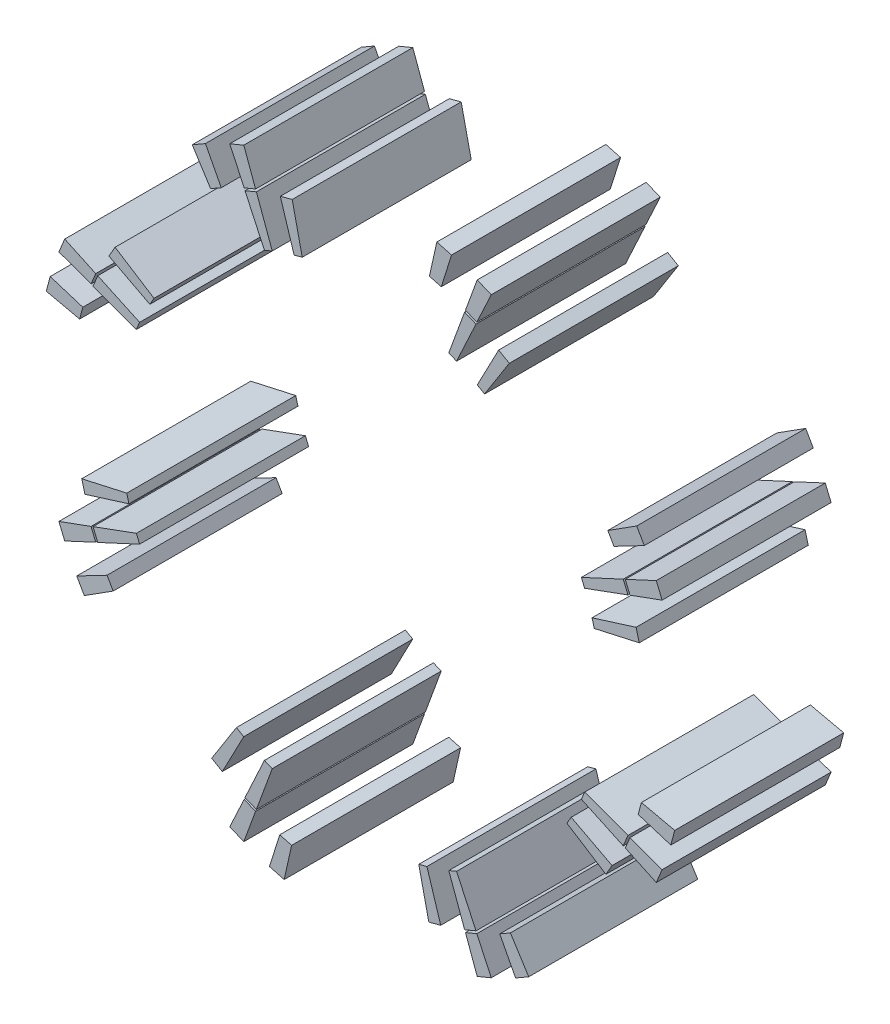
SolidWorks part; units mm, degrees
ref_plane "Спереди" through (0, 0, 0) normal (0, 0, 1) x (1, 0, 0)
ref_plane "Сверху" through (0, 0, 0) normal (0, 1, 0) x (1, 0, 0)
ref_plane "Справа" through (0, 0, 0) normal (1, 0, 0) x (0, 0, -1)
sketch "Эскиз1" plane through (0, 0, 0) normal (0, 0, 1) x (1, 0, 0)
  line L0 (41.4922, 10.3414) -> (49.4854, 12.1292)
  line L1 (49.4854, 12.1292) -> (48.9202, 14.2385)
  line L2 (48.9202, 14.2385) -> (41.104, 11.7902)
  line L3 (41.104, 11.7902) -> (41.4922, 10.3414)
  line L4 (47.8376, 18.6332) -> (53.5402, 20.7158)
  line L5 (53.5402, 20.7158) -> (52.507, 23.2103)
  line L6 (52.507, 23.2103) -> (47.002, 20.6506)
  line L7 (47.002, 20.6506) -> (47.8376, 18.6332)
  line L8 (39.7874, 15.6687) -> (47.4788, 18.4846)
  line L9 (47.4788, 18.4846) -> (46.6432, 20.502)
  line L10 (46.6432, 20.502) -> (39.2134, 17.0545)
  line L11 (39.2134, 17.0545) -> (39.7874, 15.6687)
  line L12 (44.9963, 24.7179) -> (50.3782, 27.527)
  line L13 (50.3782, 27.527) -> (49.0282, 29.8653)
  line L14 (49.0282, 29.8653) -> (43.9044, 26.609)
  line L15 (43.9044, 26.609) -> (44.9963, 24.7179)
  line L16 (22.027, 36.6519) -> (26.4148, 43.5681)
  line L17 (26.4148, 43.5681) -> (24.5237, 44.6599)
  line L18 (24.5237, 44.6599) -> (20.728, 37.4019)
  line L19 (20.728, 37.4019) -> (22.027, 36.6519)
  line L20 (20.6506, 47.002) -> (23.2103, 52.507)
  line L21 (23.2103, 52.507) -> (20.7158, 53.5402)
  line L22 (20.7158, 53.5402) -> (18.6332, 47.8376)
  line L23 (18.6332, 47.8376) -> (20.6506, 47.002)
  line L24 (17.0545, 39.2134) -> (20.502, 46.6432)
  line L25 (20.502, 46.6432) -> (18.4846, 47.4788)
  line L26 (18.4846, 47.4788) -> (15.6687, 39.7874)
  line L27 (15.6687, 39.7874) -> (17.0545, 39.2134)
  line L28 (14.339, 49.2953) -> (16.1582, 55.0873)
  line L29 (16.1582, 55.0873) -> (13.5502, 55.7861)
  line L30 (13.5502, 55.7861) -> (12.2298, 49.8605)
  line L31 (12.2298, 49.8605) -> (14.339, 49.2953)
  line L32 (-10.3414, 41.4922) -> (-12.1292, 49.4854)
  line L33 (-12.1292, 49.4854) -> (-14.2385, 48.9202)
  line L34 (-14.2385, 48.9202) -> (-11.7902, 41.104)
  line L35 (-11.7902, 41.104) -> (-10.3414, 41.4922)
  line L36 (-18.6332, 47.8376) -> (-20.7158, 53.5402)
  line L37 (-20.7158, 53.5402) -> (-23.2103, 52.507)
  line L38 (-23.2103, 52.507) -> (-20.6506, 47.002)
  line L39 (-20.6506, 47.002) -> (-18.6332, 47.8376)
  line L40 (-15.6687, 39.7874) -> (-18.4846, 47.4788)
  line L41 (-18.4846, 47.4788) -> (-20.502, 46.6432)
  line L42 (-20.502, 46.6432) -> (-17.0545, 39.2134)
  line L43 (-17.0545, 39.2134) -> (-15.6687, 39.7874)
  line L44 (-24.7179, 44.9963) -> (-27.527, 50.3782)
  line L45 (-27.527, 50.3782) -> (-29.8653, 49.0282)
  line L46 (-29.8653, 49.0282) -> (-26.609, 43.9044)
  line L47 (-26.609, 43.9044) -> (-24.7179, 44.9963)
  line L48 (-36.6519, 22.027) -> (-43.5681, 26.4148)
  line L49 (-43.5681, 26.4148) -> (-44.6599, 24.5237)
  line L50 (-44.6599, 24.5237) -> (-37.4019, 20.728)
  line L51 (-37.4019, 20.728) -> (-36.6519, 22.027)
  line L52 (-47.002, 20.6506) -> (-52.507, 23.2103)
  line L53 (-52.507, 23.2103) -> (-53.5402, 20.7158)
  line L54 (-53.5402, 20.7158) -> (-47.8376, 18.6332)
  line L55 (-47.8376, 18.6332) -> (-47.002, 20.6506)
  line L56 (-39.2134, 17.0545) -> (-46.6432, 20.502)
  line L57 (-46.6432, 20.502) -> (-47.4788, 18.4846)
  line L58 (-47.4788, 18.4846) -> (-39.7874, 15.6687)
  line L59 (-39.7874, 15.6687) -> (-39.2134, 17.0545)
  line L60 (-49.2953, 14.339) -> (-55.0873, 16.1582)
  line L61 (-55.0873, 16.1582) -> (-55.7861, 13.5502)
  line L62 (-55.7861, 13.5502) -> (-49.8605, 12.2298)
  line L63 (-49.8605, 12.2298) -> (-49.2953, 14.339)
  line L64 (-41.4922, -10.3414) -> (-49.4854, -12.1292)
  line L65 (-49.4854, -12.1292) -> (-48.9202, -14.2385)
  line L66 (-48.9202, -14.2385) -> (-41.104, -11.7902)
  line L67 (-41.104, -11.7902) -> (-41.4922, -10.3414)
  line L68 (-47.8376, -18.6332) -> (-53.5402, -20.7158)
  line L69 (-53.5402, -20.7158) -> (-52.507, -23.2103)
  line L70 (-52.507, -23.2103) -> (-47.002, -20.6506)
  line L71 (-47.002, -20.6506) -> (-47.8376, -18.6332)
  line L72 (-39.7874, -15.6687) -> (-47.4788, -18.4846)
  line L73 (-47.4788, -18.4846) -> (-46.6432, -20.502)
  line L74 (-46.6432, -20.502) -> (-39.2134, -17.0545)
  line L75 (-39.2134, -17.0545) -> (-39.7874, -15.6687)
  line L76 (-44.9963, -24.7179) -> (-50.3782, -27.527)
  line L77 (-50.3782, -27.527) -> (-49.0282, -29.8653)
  line L78 (-49.0282, -29.8653) -> (-43.9044, -26.609)
  line L79 (-43.9044, -26.609) -> (-44.9963, -24.7179)
  line L80 (-22.027, -36.6519) -> (-26.4148, -43.5681)
  line L81 (-26.4148, -43.5681) -> (-24.5237, -44.6599)
  line L82 (-24.5237, -44.6599) -> (-20.728, -37.4019)
  line L83 (-20.728, -37.4019) -> (-22.027, -36.6519)
  line L84 (-20.6506, -47.002) -> (-23.2103, -52.507)
  line L85 (-23.2103, -52.507) -> (-20.7158, -53.5402)
  line L86 (-20.7158, -53.5402) -> (-18.6332, -47.8376)
  line L87 (-18.6332, -47.8376) -> (-20.6506, -47.002)
  line L88 (-17.0545, -39.2134) -> (-20.502, -46.6432)
  line L89 (-20.502, -46.6432) -> (-18.4846, -47.4788)
  line L90 (-18.4846, -47.4788) -> (-15.6687, -39.7874)
  line L91 (-15.6687, -39.7874) -> (-17.0545, -39.2134)
  line L92 (-14.339, -49.2953) -> (-16.1582, -55.0873)
  line L93 (-16.1582, -55.0873) -> (-13.5502, -55.7861)
  line L94 (-13.5502, -55.7861) -> (-12.2298, -49.8605)
  line L95 (-12.2298, -49.8605) -> (-14.339, -49.2953)
  line L96 (10.3414, -41.4922) -> (12.1292, -49.4854)
  line L97 (12.1292, -49.4854) -> (14.2385, -48.9202)
  line L98 (14.2385, -48.9202) -> (11.7902, -41.104)
  line L99 (11.7902, -41.104) -> (10.3414, -41.4922)
  line L100 (18.6332, -47.8376) -> (20.7158, -53.5402)
  line L101 (20.7158, -53.5402) -> (23.2103, -52.507)
  line L102 (23.2103, -52.507) -> (20.6506, -47.002)
  line L103 (20.6506, -47.002) -> (18.6332, -47.8376)
  line L104 (15.6687, -39.7874) -> (18.4846, -47.4788)
  line L105 (18.4846, -47.4788) -> (20.502, -46.6432)
  line L106 (20.502, -46.6432) -> (17.0545, -39.2134)
  line L107 (17.0545, -39.2134) -> (15.6687, -39.7874)
  line L108 (24.7179, -44.9963) -> (27.527, -50.3782)
  line L109 (27.527, -50.3782) -> (29.8653, -49.0282)
  line L110 (29.8653, -49.0282) -> (26.609, -43.9044)
  line L111 (26.609, -43.9044) -> (24.7179, -44.9963)
  line L112 (36.6519, -22.027) -> (43.5681, -26.4148)
  line L113 (43.5681, -26.4148) -> (44.6599, -24.5237)
  line L114 (44.6599, -24.5237) -> (37.4019, -20.728)
  line L115 (37.4019, -20.728) -> (36.6519, -22.027)
  line L116 (47.002, -20.6506) -> (52.507, -23.2103)
  line L117 (52.507, -23.2103) -> (53.5402, -20.7158)
  line L118 (53.5402, -20.7158) -> (47.8376, -18.6332)
  line L119 (47.8376, -18.6332) -> (47.002, -20.6506)
  line L120 (39.2134, -17.0545) -> (46.6432, -20.502)
  line L121 (46.6432, -20.502) -> (47.4788, -18.4846)
  line L122 (47.4788, -18.4846) -> (39.7874, -15.6687)
  line L123 (39.7874, -15.6687) -> (39.2134, -17.0545)
  line L124 (49.2953, -14.339) -> (55.0873, -16.1582)
  line L125 (55.0873, -16.1582) -> (55.7861, -13.5502)
  line L126 (55.7861, -13.5502) -> (49.8605, -12.2298)
  line L127 (49.8605, -12.2298) -> (49.2953, -14.339)
extrude "Slot_copper_envelopes" add sketch "Эскиз1" along normal blind 30 from offset 15 separate body
